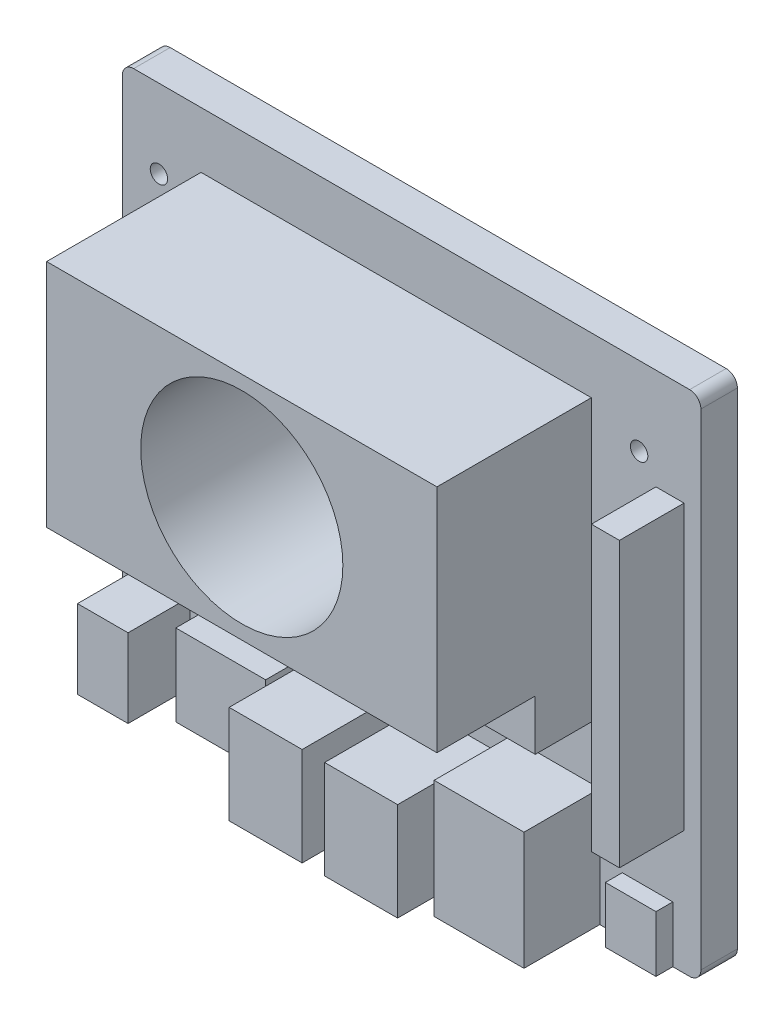
SolidWorks part; units mm, degrees
ref_plane "前视基准面" through (0, 0, 0) normal (0, 0, 1) x (1, 0, 0)
ref_plane "上视基准面" through (0, 0, 0) normal (0, 1, 0) x (1, 0, 0)
ref_plane "右视基准面" through (0, 0, 0) normal (1, 0, 0) x (0, 0, -1)
other "Configuration Table"
sketch "草图1" plane through (0, 0, 0) normal (0, 0, 1) x (1, 0, 0)
  line L1 (0, 0) -> (103, 0)
  line L2 (0, 0) -> (0, 90.5)
  line L3 (0, 90.5) -> (103, 90.5)
  line L4 (103, 0) -> (103, 90.5)
  dimension "D1" = 103
  dimension "D2" = 90.5
extrude "凸台-拉伸1" add sketch "草图1" along normal blind 6.5
sketch "草图2" plane through (0, 0, 6.5) normal (0, 0, 1) x (1, 0, 0)
  line L2 (0, 0) -> (103, 0) construction
  line L3 (3, 0) -> (3, 14)
  line L4 (3, 14) -> (12, 14)
  line L5 (12, 14) -> (12, 0)
  line L7 (16, 0) -> (16, 14.5)
  line L8 (16, 14.5) -> (32, 14.5)
  line L9 (32, 14.5) -> (32, 0)
  line L11 (36, 0) -> (36, 17.5)
  line L12 (36, 17.5) -> (49, 17.5)
  line L13 (49, 17.5) -> (49, 0)
  line L15 (53, 0) -> (53, 17.5)
  line L16 (53, 17.5) -> (66, 17.5)
  line L17 (66, 17.5) -> (66, 0)
  line L19 (69, 0) -> (69, 21)
  line L20 (69, 21) -> (85, 21)
  line L21 (85, 21) -> (85, 0)
  line L23 (89, 0) -> (89, 10)
  line L24 (89, 10) -> (98, 10)
  line L25 (98, 10) -> (98, 0)
  line L38 (3, 0) -> (12, 0)
  line L39 (16, 0) -> (32, 0)
  line L40 (36, 0) -> (49, 0)
  line L41 (53, 0) -> (66, 0)
  line L42 (69, 0) -> (85, 0)
  line L43 (89, 0) -> (98, 0)
  line L44 (0, 90.5) -> (0, 0) construction
  line L45 (14, 80.5) -> (83.5, 80.5)
  line L46 (14, 80.5) -> (14, 30.5)
  line L47 (14, 30.5) -> (83.5, 30.5)
  line L48 (83.5, 80.5) -> (83.5, 30.5)
  line L49 (90, 67.5) -> (92.5, 67.5)
  line L50 (90, 67.5) -> (90, 48.5)
  line L51 (90, 48.5) -> (92.5, 48.5)
  line L52 (92.5, 67.5) -> (92.5, 48.5)
  line L53 (95, 72.5) -> (100, 72.5)
  line L54 (95, 72.5) -> (95, 22)
  line L55 (95, 22) -> (100, 22)
  line L56 (100, 72.5) -> (100, 22)
  line L57 (103, 0) -> (103, 90.5) construction
  line L59 (14, 60) -> (83.5, 60) construction
  circle A0 centre (48.75, 60) radius 18
  dimension "D27" = 36
  dimension "D1" = 16
  dimension "D2" = 21
  dimension "D3" = 17.5
  dimension "D4" = 17.5
  dimension "D5" = 14.5
  dimension "D6" = 10
  dimension "D7" = 14
  dimension "D8" = 13
  dimension "D9" = 13
  dimension "D10" = 16
  dimension "D11" = 9
  dimension "D12" = 3
  dimension "D13" = 4
  dimension "D14" = 4
  dimension "D15" = 4
  dimension "D16" = 3
  dimension "D17" = 5
  dimension "D18" = 9
  dimension "D19" = 50
  dimension "D20" = 13
  dimension "D21" = 14
  dimension "D22" = 69.5
  dimension "D23" = 72.5
  dimension "D24" = 50.5
  dimension "D25" = 5
  dimension "D26" = 3
  dimension "D28" = 13
  dimension "D29" = 2.5
  dimension "D30" = 5
  dimension "D31" = 19
  dimension "D32" = 20.5
extrude "凸台-拉伸2" add sketch "草图2" along normal blind 27.5
sketch "草图3" plane through (0, 0, 0) normal (0, -1, 0) x (1, 0, 0)
  line L0 (12, 34) -> (12, 6.5) construction
  line L1 (3, 34) -> (12, 34)
  line L2 (3, 34) -> (3, 17.5)
  line L3 (3, 17.5) -> (12, 17.5)
  line L4 (12, 34) -> (12, 17.5)
  line L5 (0, 0) -> (103, 0) construction
  line L6 (32, 34) -> (32, 6.5) construction
  line L7 (16, 34) -> (32, 34)
  line L8 (16, 34) -> (16, 13)
  line L9 (16, 13) -> (32, 13)
  line L10 (32, 34) -> (32, 13)
  line L12 (49, 34) -> (49, 6.5) construction
  line L13 (36, 34) -> (49, 34)
  line L14 (36, 34) -> (36, 23.5)
  line L15 (36, 23.5) -> (49, 23.5)
  line L16 (49, 34) -> (49, 23.5)
  line L17 (66, 34) -> (66, 6.5) construction
  line L18 (53, 34) -> (66, 34)
  line L19 (53, 34) -> (53, 23.5)
  line L20 (53, 23.5) -> (66, 23.5)
  line L21 (66, 34) -> (66, 23.5)
  line L22 (85, 34) -> (85, 6.5) construction
  line L23 (69, 34) -> (85, 34)
  line L24 (69, 34) -> (69, 20)
  line L25 (69, 20) -> (85, 20)
  line L26 (85, 34) -> (85, 20)
  line L27 (98, 34) -> (98, 6.5) construction
  line L28 (89, 34) -> (98, 34)
  line L29 (89, 34) -> (89, 9.5)
  line L30 (89, 9.5) -> (98, 9.5)
  line L31 (98, 34) -> (98, 9.5)
  dimension "D1" = 17.5
  dimension "D2" = 13
  dimension "D3" = 23.5
  dimension "D4" = 23.5
  dimension "D5" = 20
  dimension "D6" = 9.5
extrude "切除-拉伸1" cut sketch "草图3" against normal up to next
sketch "草图4" plane through (0, 0, 34) normal (0, 0, 1) x (1, 0, 0)
  line L0 (14, 80.5) -> (14, 30.5) construction
  line L1 (14, 39.5) -> (83.5, 39.5)
  line L2 (14, 39.5) -> (14, 30.5)
  line L3 (14, 30.5) -> (83.5, 30.5)
  line L4 (83.5, 39.5) -> (83.5, 30.5)
  line L5 (83.5, 80.5) -> (14, 80.5) construction
  dimension "D1" = 41
extrude "切除-拉伸2" cut sketch "草图4" against normal blind 17.5
sketch "草图5" plane through (0, 0, 6.5) normal (0, 0, 1) x (1, 0, 0)
  line L0 (103, 0) -> (103, 90.5) construction
  line L1 (89, 0) -> (98, 0) construction
  line L2 (103, 90.5) -> (0, 90.5) construction
  circle A0 centre (92, 19) radius 1.55
  circle A1 centre (92, 76.5) radius 1.55
  circle A2 centre (6.5, 76.5) radius 1.55
  circle A3 centre (6.5, 19.5) radius 1.55
  dimension "D5" = 3.1
  dimension "D6" = 3.1
  dimension "D9" = 3.1
  dimension "D11" = 3.1
  dimension "D1" = 11
  dimension "D2" = 19
  dimension "D3" = 11
  dimension "D4" = 14
  dimension "D7" = 14
  dimension "D8" = 85.5
  dimension "D10" = 57
  dimension "D12" = 85.5
extrude "切除-拉伸3" cut sketch "草图5" against normal through all
sketch "草图6" plane through (92.5, 0, 0) normal (1, 0, 0) x (0, 0, -1)
  line L0 (0, 0) -> (0, 90.5) construction
  line L1 (-34, 67.5) -> (-13, 67.5)
  line L2 (-34, 67.5) -> (-34, 48.5)
  line L3 (-34, 48.5) -> (-13, 48.5)
  line L4 (-13, 67.5) -> (-13, 48.5)
  dimension "D1" = 13
extrude "切除-拉伸4" cut sketch "草图6" against normal up to next
sketch "草图7" plane through (100, 0, 0) normal (1, 0, 0) x (0, 0, -1)
  line L6 (-34, 22) -> (-6.5, 22) construction
  line L7 (-34, 72.5) -> (-18, 72.5)
  line L8 (-34, 72.5) -> (-34, 22)
  line L9 (-34, 22) -> (-18, 22)
  line L10 (-18, 72.5) -> (-18, 22)
  line L11 (0, 0) -> (0, 90.5) construction
  dimension "D1" = 18
extrude "切除-拉伸5" cut sketch "草图7" against normal up to next
fillet "圆角1" radius 2 4 edges at (0, 0, 3.25) (0, 90.5, 3.25) (103, 0, 3.25) (103, 90.5, 3.25)
